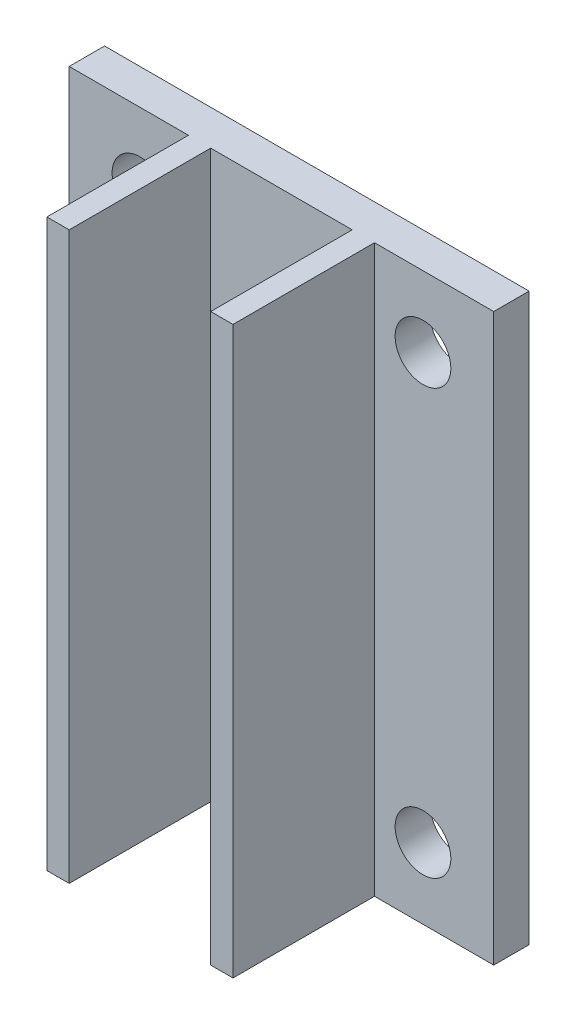
SolidWorks part; units mm, degrees
ref_plane "Front Plane" through (0, 0, 0) normal (0, 0, 1) x (1, 0, 0)
ref_plane "Top Plane" through (0, 0, 0) normal (0, 1, 0) x (1, 0, 0)
ref_plane "Right Plane" through (0, 0, 0) normal (1, 0, 0) x (0, 0, -1)
sketch "Sketch1" plane through (0, 0, 0) normal (0, 1, 0) x (1, 0, 0)
  line L0 (-12.7, 0) -> (12.7, 0)
  line L1 (12.7, 0) -> (12.7, -25.4)
  line L2 (12.7, -25.4) -> (16.7, -25.4)
  line L3 (16.7, -25.4) -> (16.7, 0)
  line L4 (16.7, 0) -> (38.1, 0)
  line L5 (38.1, 0) -> (38.1, 6.35)
  line L6 (38.1, 6.35) -> (-38.1, 6.35)
  line L7 (-38.1, 6.35) -> (-38.1, 0)
  line L8 (-38.1, 0) -> (-16.7, 0)
  line L9 (-16.7, 0) -> (-16.7, -25.4)
  line L10 (-16.7, -25.4) -> (-12.7, -25.4)
  line L11 (-12.7, -25.4) -> (-12.7, 0)
  point P4 (0, 0)
  dimension "D1" = 25.4
  dimension "D2" = 6.35
  dimension "D3" = 76.2
  dimension "D4" = 4
extrude "Boss-Extrude1" add sketch "Sketch1" along normal blind 101.6
sketch "Sketch2" plane through (0, 0, -6.35) normal (0, 0, -1) x (-1, 0, 0)
  line L0 (-25.4, 88.9) -> (25.4, 88.9) construction
  line L1 (0, 88.9) -> (0, 0) construction
  line L2 (-38.1, 0) -> (38.1, 0) construction
  line L3 (-38.1, 101.6) -> (38.1, 101.6) construction
  line L4 (-25.4, 12.7) -> (0, 12.7) construction
  line L5 (0, 12.7) -> (25.4, 12.7) construction
  line L6 (-25.4, 88.9) -> (-25.4, 12.7) construction
  circle A0 centre (-25.4, 88.9) radius 5
  circle A1 centre (25.4, 88.9) radius 5
  circle A2 centre (-25.4, 12.7) radius 5
  circle A3 centre (25.4, 12.7) radius 5
  dimension "D2" = 10
  dimension "D1" = 50.8
  dimension "D3" = 12.7
  dimension "D4" = 12.7
extrude "Cut-Extrude1" cut sketch "Sketch2" against normal through all
